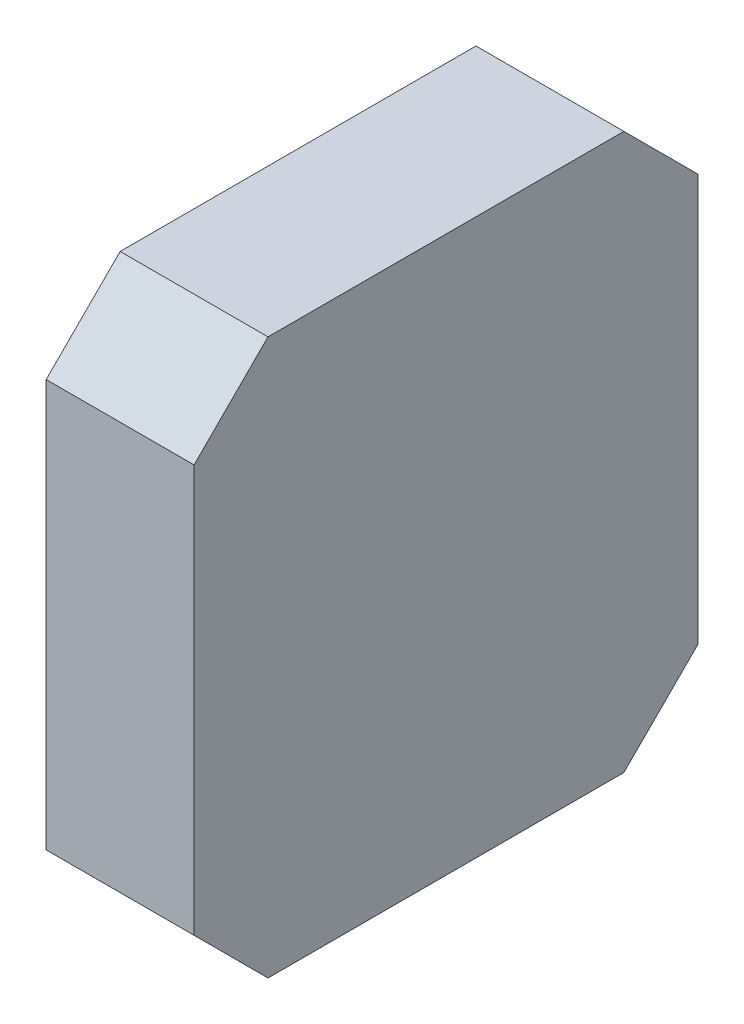
SolidWorks part; units mm, degrees
ref_plane "Front Plane" through (0, 0, 0) normal (0, 0, 1) x (1, 0, 0)
ref_plane "Top Plane" through (0, 0, 0) normal (0, 1, 0) x (1, 0, 0)
ref_plane "Right Plane" through (0, 0, 0) normal (1, 0, 0) x (0, 0, -1)
sketch "Sketch3" plane through (0, 0, 0) normal (1, 0, 0) x (0, 0, -1)
  line L0 (-68.12, -75.085) -> (68.12, -75.085)
  line L1 (-68.12, -75.085) -> (-68.12, 75.085)
  line L2 (68.12, -75.085) -> (68.12, 75.085)
  line L3 (-68.12, 75.085) -> (68.12, 75.085)
  line L4 (-68.12, -75.085) -> (68.12, 75.085) construction
  line L5 (68.12, -75.085) -> (-68.12, 75.085) construction
  point P1 (0, 0)
extrude "Boss-Extrude1" add sketch "Sketch3" along normal blind 30
sketch "Sketch4" plane through (0, 0, 0) normal (-1, 0, 0) x (0, 0, 1)
  line L1 (-68.12, 75.085) -> (-48.12, 75.085)
  line L3 (-68.12, 75.085) -> (68.12, 75.085) construction
  line L4 (-68.12, 75.085) -> (-68.12, 55.085)
  line L7 (-68.12, -75.085) -> (-68.12, 75.085) construction
  line L13 (-68.12, 55.085) -> (-48.12, 75.085)
  line L14 (68.12, 75.085) -> (68.12, 55.085)
  line L15 (68.12, 75.085) -> (68.12, -75.085) construction
  line L16 (68.12, 75.085) -> (48.12, 75.085)
  line L17 (-68.12, -75.085) -> (-68.12, -55.085)
  line L18 (-68.12, -75.085) -> (-48.12, -75.085)
  line L19 (68.12, -75.085) -> (-68.12, -75.085) construction
  line L20 (68.12, -75.085) -> (68.12, -55.085)
  line L21 (68.12, -75.085) -> (48.12, -75.085)
  line L22 (-48.12, -75.085) -> (-68.12, -55.085)
  line L23 (48.12, -75.085) -> (68.12, -55.085)
  line L24 (68.12, 55.085) -> (48.12, 75.085)
  line L25 (25.4958, -20) -> (29.4958, -20)
  line L27 (-4.5042, -20) -> (-4.5042, -40)
  line L28 (-4.5042, -20) -> (25.4958, -20)
  line L29 (-4.5042, -40) -> (25.4958, -40)
  line L31 (29.4958, -20) -> (29.4958, -40)
  line L32 (29.4958, -40) -> (25.4958, -40)
extrude "Cut-Extrude1" cut sketch "Sketch4" against normal blind 30
sketch "Sketch6" plane through (30, 0, 0) normal (1, 0, 0) x (0, 0, -1)
  line L0 (-68.12, 55.085) -> (-48.12, 75.085)
  line L1 (-48.12, 75.085) -> (48.12, 75.085)
  line L2 (48.12, 75.085) -> (68.12, 55.085)
  line L3 (68.12, 55.085) -> (68.12, -55.085)
  line L4 (68.12, -55.085) -> (48.12, -75.085)
  line L5 (48.12, -75.085) -> (-48.12, -75.085)
  line L6 (-48.12, -75.085) -> (-68.12, -55.085)
  line L7 (-68.12, -55.085) -> (-68.12, 55.085)
extrude "Boss-Extrude2" add sketch "Sketch6" along normal blind 10
